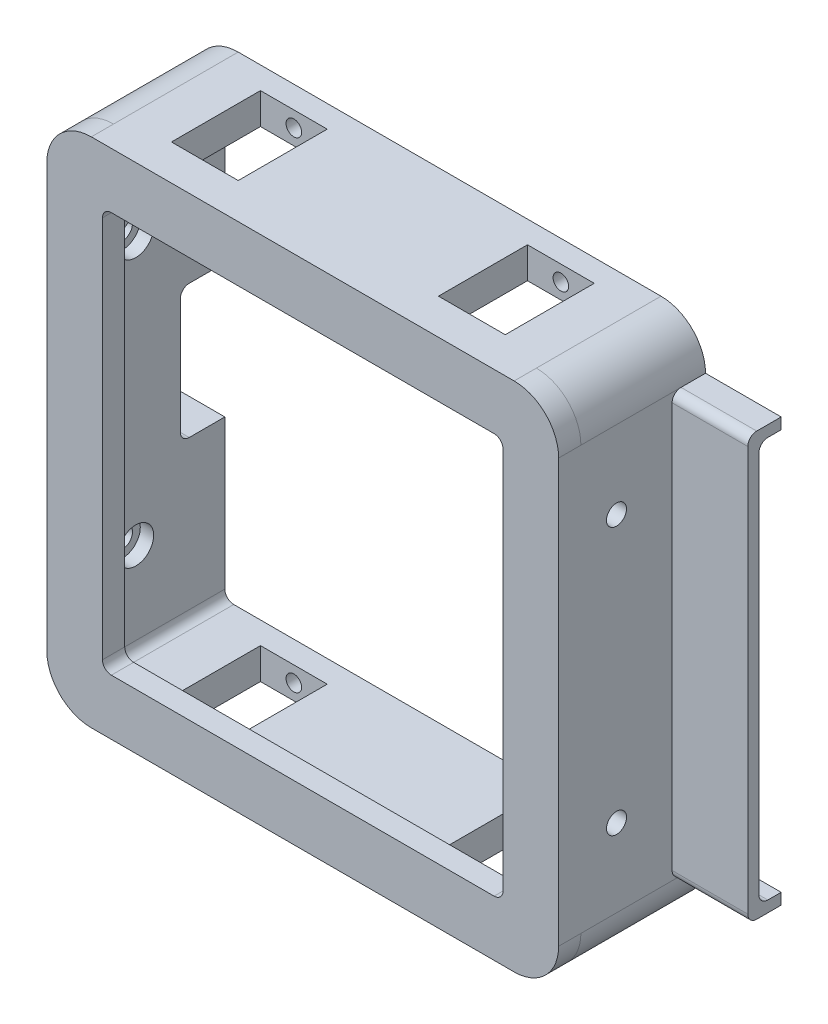
SolidWorks part; units mm, degrees
ref_plane "Front Plane" through (0, 0, 0) normal (0, 0, 1) x (1, 0, 0)
ref_plane "Top Plane" through (0, 0, 0) normal (0, 1, 0) x (1, 0, 0)
ref_plane "Right Plane" through (0, 0, 0) normal (1, 0, 0) x (0, 0, -1)
sketch "Sketch1" plane through (0, 0, 0) normal (0, 0, 1) x (1, 0, 0)
  line L1 (57.5, -57.5) -> (-57.5, -57.5)
  line L2 (57.5, -57.5) -> (57.5, 57.5)
  line L3 (57.5, 57.5) -> (-57.5, 57.5)
  line L4 (-57.5, -57.5) -> (-57.5, 57.5)
  line L5 (57.5, -57.5) -> (-57.5, 57.5) construction
  line L6 (57.5, 57.5) -> (-57.5, -57.5) construction
  point P0 (0, 0)
  dimension "D1" = 115
  dimension "D2" = 115
extrude "Boss-Extrude1" add sketch "Sketch1" along normal blind 28
fillet "Fillet1" radius 10 4 edges at (-57.5, -57.5, 14) (57.5, -57.5, 14) (-57.5, 57.5, 14) (57.5, 57.5, 14)
ref_plane "Plane1" through (0, 0, 28) normal (0, 0, 1) x (1, 0, 0)
sketch "Sketch2" plane through (0, 0, 28) normal (0, 0, 1) x (1, 0, 0)
  line L1 (50.5, -50.5) -> (-50.5, -50.5)
  line L2 (50.5, -50.5) -> (50.5, 50.5)
  line L3 (50.5, 50.5) -> (-50.5, 50.5)
  line L4 (-50.5, -50.5) -> (-50.5, 50.5)
  line L5 (50.5, -50.5) -> (-50.5, 50.5) construction
  line L6 (50.5, 50.5) -> (-50.5, -50.5) construction
  point P0 (0, 0)
  dimension "D1" = 101
  dimension "D2" = 101
extrude "Cut-Extrude1" cut sketch "Sketch2" against normal blind 30
fillet "Fillet2" radius 2 4 edges at (50.5, -50.5, 14) (-50.5, -50.5, 14) (50.5, 50.5, 14) (-50.5, 50.5, 14)
ref_plane "Plane2" through (57.5, 0, 0) normal (1, 0, 0) x (0, 0, -1)
sketch "Sketch3" plane through (57.5, 0, 0) normal (1, 0, 0) x (0, 0, -1)
  line L1 (5, -45) -> (-5, -45)
  line L2 (5, -45) -> (5, 45)
  line L3 (5, 45) -> (-5, 45)
  line L4 (-5, -45) -> (-5, 45)
  line L5 (5, -45) -> (-5, 45) construction
  line L6 (5, 45) -> (-5, -45) construction
  point P0 (0, 0)
  dimension "D1" = 10
  dimension "D2" = 90
extrude "Cut-Extrude2" cut sketch "Sketch3" against normal blind 30
sketch "Sketch4" plane through (57.5, 0, 0) normal (1, 0, 0) x (0, 0, -1)
  line L0 (-28, -47.5) -> (0, -47.5) construction
  line L1 (-5, 45) -> (0, 45)
  line L2 (-5, 45) -> (-5, 47.5)
  line L3 (-5, 47.5) -> (0, 47.5)
  line L4 (0, 45) -> (0, 47.5)
  line L5 (-5, -45) -> (0, -45)
  line L6 (-5, -45) -> (-5, -47.5)
  line L7 (-5, -47.5) -> (0, -47.5)
  line L8 (0, -45) -> (0, -47.5)
  line L9 (-5, 47.5) -> (-7.5, 47.5)
  line L10 (-5, 47.5) -> (-5, -47.5)
  line L11 (-5, -47.5) -> (-7.5, -47.5)
  line L12 (-7.5, 47.5) -> (-7.5, -47.5)
  dimension "D1" = 2.5
extrude "Boss-Extrude2" add sketch "Sketch4" along normal blind 17 contours L9 L12 L11 L6 L10 L2 | L1 L4 L3 L2 | L8 L5 L6 L7
fillet "Fillet3" radius 2 4 edges at (62.5, -45, 5) (66, -47.5, 7.5) (62.5, 45, 5) (66, 47.5, 7.5)
ref_plane "Plane3" through (-57.5, 0, 0) normal (-1, 0, 0) x (0, 0, 1)
sketch "Sketch5" plane through (-57.5, 0, 0) normal (-1, 0, 0) x (0, 0, 1)
  line L1 (10, -15) -> (-10, -15)
  line L2 (10, -15) -> (10, 15)
  line L3 (10, 15) -> (-10, 15)
  line L4 (-10, -15) -> (-10, 15)
  line L5 (10, -15) -> (-10, 15) construction
  line L6 (10, 15) -> (-10, -15) construction
  point P0 (0, 0)
  dimension "D1" = 30
  dimension "D2" = 20
extrude "Cut-Extrude3" cut sketch "Sketch5" against normal blind 22
sketch "Sketch6" plane through (-57.5, 0, 0) normal (-1, 0, 0) x (0, 0, 1)
  line L0 (0, 47.5) -> (0, 15) construction
  line L1 (10, 15) -> (0, 15)
  line L2 (10, 15) -> (10, 17.5)
  line L3 (10, 17.5) -> (0, 17.5)
  line L4 (0, 15) -> (0, 17.5)
  line L5 (0, -15) -> (0, -47.5) construction
  line L6 (10, -15) -> (0, -15)
  line L7 (10, -15) -> (10, -17.5)
  line L8 (10, -17.5) -> (0, -17.5)
  line L9 (0, -15) -> (0, -17.5)
  line L11 (10, 17.5) -> (12.5, 17.5)
  line L12 (10, 17.5) -> (10, -17.5)
  line L13 (10, -17.5) -> (12.5, -17.5)
  line L14 (12.5, 17.5) -> (12.5, -17.5)
  dimension "D1" = 2.5
  dimension "D2" = 2.5
  dimension "D3" = 2.5
extrude "Boss-Extrude3" add sketch "Sketch6" along normal blind 19 contours L14 L11 L2 L12 L7 L13 | L4 L1 L2 L3 | L6 L9 L8 L7
fillet "Fillet4" radius 2 4 edges at (-63.5, -15, 10) (-67, -17.5, 12.5) (-63.5, 15, 10) (-67, 17.5, 12.5)
ref_plane "Plane4" through (0, 57.5, 0) normal (0, 1, 0) x (1, 0, 0)
sketch "Sketch7" plane through (0, 57.5, 0) normal (0, 1, 0) x (1, 0, 0)
  line L5 (-37.5, -5) -> (-22.5, -5)
  line L6 (-37.5, -5) -> (-37.5, -25)
  line L7 (-37.5, -25) -> (-22.5, -25)
  line L8 (-22.5, -5) -> (-22.5, -25)
  line L9 (-37.5, -5) -> (-22.5, -25) construction
  line L10 (-37.5, -25) -> (-22.5, -5) construction
  line L11 (37.5, -25) -> (22.5, -25)
  line L12 (37.5, -25) -> (37.5, -5)
  line L13 (37.5, -5) -> (22.5, -5)
  line L14 (22.5, -25) -> (22.5, -5)
  line L15 (37.5, -25) -> (22.5, -5) construction
  line L16 (37.5, -5) -> (22.5, -25) construction
  point P0 (-30, -15)
  point P5 (30, -15)
  dimension "D1" = 20
  dimension "D2" = 15
  dimension "D3" = 15
  dimension "D4" = 15
  dimension "D5" = 30
  dimension "D6" = 30
  dimension "D7" = 15
  dimension "D8" = 20
extrude "Cut-Extrude4" cut sketch "Sketch7" against normal blind 120
ref_plane "Plane5" through (0, 0, 0) normal (0, 0, -1) x (-1, 0, 0)
sketch "Sketch9" plane through (0, 0, 0) normal (0, 0, -1) x (-1, 0, 0)
  circle A0 centre (-30, 54) radius 1.75
  dimension "D1" = 3.5
  dimension "D2" = 30
  dimension "D3" = 54
extrude "Cut-Extrude6" cut sketch "Sketch9" against normal blind 10
mirror "Mirror2" about plane through (0, 0, 0) normal (1, 0, 0) of "Cut-Extrude6" second plane through (0, 0, 0) second plane normal (0, 1, 0)
sketch "Sketch11" plane through (-57.5, 0, 0) normal (-1, 0, 0) x (0, 0, 1)
  circle A0 centre (20, 30) radius 2.25
  dimension "D1" = 4.5
  dimension "D2" = 20
  dimension "D3" = 30
extrude "Cut-Extrude7" cut sketch "Sketch11" against normal blind 125
mirror "Mirror3" about plane through (0, 0, 0) normal (0, 1, 0) of "Cut-Extrude7"
ref_plane "Plane6" through (-50.5, 0, 0) normal (1, 0, 0) x (0, 0, -1)
sketch "Sketch12" plane through (-50.5, 0, 0) normal (1, 0, 0) x (0, 0, -1)
  circle A0 centre (-20, 30) radius 4
  dimension "D1" = 8
extrude "Cut-Extrude8" cut sketch "Sketch12" against normal blind 3
mirror "Mirror4" about plane through (0, 0, 0) normal (1, 0, 0) of "Cut-Extrude8" second plane through (0, 0, 0) second plane normal (0, 1, 0)
sketch "Sketch14" plane through (0, 0, 28) normal (0, 0, 1) x (1, 0, 0)
  line L1 (57.5, -57.5) -> (-57.5, -57.5)
  line L2 (57.5, -57.5) -> (57.5, 57.5)
  line L3 (57.5, 57.5) -> (-57.5, 57.5)
  line L4 (-57.5, -57.5) -> (-57.5, 57.5)
  line L5 (57.5, -57.5) -> (-57.5, 57.5) construction
  line L6 (57.5, 57.5) -> (-57.5, -57.5) construction
  line L7 (45, -45) -> (-45, -45)
  line L8 (45, -45) -> (45, 45)
  line L9 (45, 45) -> (-45, 45)
  line L10 (-45, -45) -> (-45, 45)
  line L11 (45, -45) -> (-45, 45) construction
  line L12 (45, 45) -> (-45, -45) construction
  point P0 (0, 0)
  point P6 (0, 0)
  dimension "D1" = 115
  dimension "D2" = 115
  dimension "D3" = 90
  dimension "D4" = 90
extrude "Boss-Extrude4" add sketch "Sketch14" along normal blind 5
fillet "Fillet5" radius 10 4 edges at (-57.5, -57.5, 30.5) (57.5, -57.5, 30.5) (-57.5, 57.5, 30.5) (57.5, 57.5, 30.5)
ref_plane "Plane7" through (0, 0, 33) normal (0, 0, 1) x (1, 0, 0)
fillet "Fillet6" radius 2 4 edges at (-45, -45, 30.5) (45, -45, 30.5) (45, 45, 30.5) (-45, 45, 30.5)
